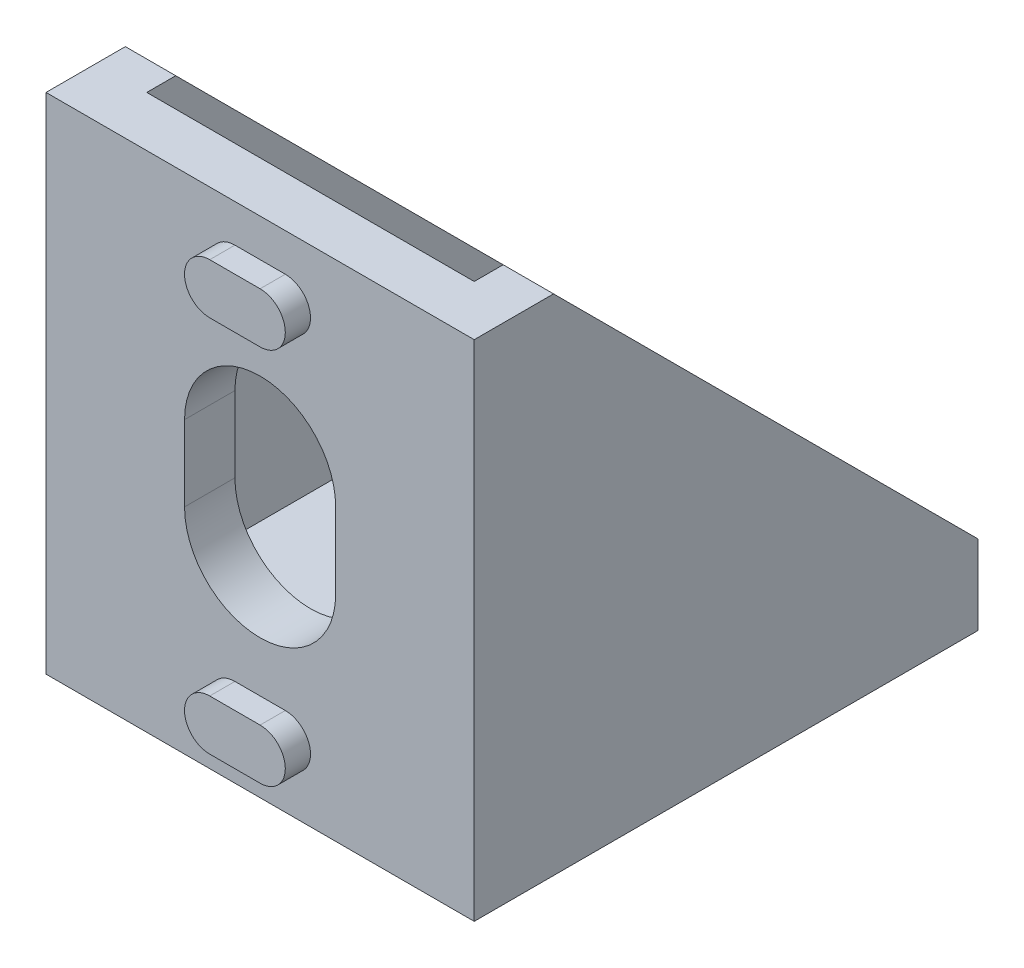
SolidWorks part; units mm, degrees
ref_plane "Front Plane" through (0, 0, 0) normal (0, 0, 1) x (1, 0, 0)
ref_plane "Top Plane" through (0, 0, 0) normal (0, 1, 0) x (1, 0, 0)
ref_plane "Right Plane" through (0, 0, 0) normal (1, 0, 0) x (0, 0, -1)
sketch "Sketch1" plane through (0, 0, 0) normal (1, 0, 0) x (0, 0, -1)
  line L0 (3.15, 20) -> (20, 3.15)
  line L1 (0, 0) -> (20, 0)
  line L2 (0, 0) -> (0, 20)
  line L3 (0, 20) -> (3.15, 20)
  line L4 (20, 0) -> (20, 3.15)
  dimension "D1" = 20
  dimension "D2" = 20
  dimension "D3" = 3.15
  dimension "D4" = 3.15
extrude "Boss-Extrude1" add sketch "Sketch1" along normal blind 2
sketch "Sketch2" plane through (2, 0, 0) normal (1, 0, 0) x (0, 0, -1)
  line L0 (0, 20) -> (0, 0) construction
  line L1 (20, 0) -> (0, 0)
  line L2 (20, 0) -> (20, 3)
  line L3 (20, 3) -> (2, 3)
  line L4 (0, 0) -> (0, 3)
  line L6 (0, 20) -> (2, 20)
  line L7 (0, 20) -> (0, 3)
  line L9 (2, 20) -> (2, 3)
  dimension "D1" = 3
  dimension "D2" = 2
extrude "Boss-Extrude2" add sketch "Sketch2" along normal blind 6.5
sketch "Sketch3" plane through (0, 0, 0) normal (0, 0, 1) x (1, 0, 0)
  line L0 (8.5, 11.5) -> (8.5, 8.5) construction
  line L1 (8.5, 20) -> (8.5, 0) construction
  line L3 (5.5, 11.5) -> (5.5, 8.5)
  line L4 (8.5, 20) -> (0, 20) construction
  line L5 (8.5, 14.5) -> (8.5, 5.5)
  arc A0 (8.5, 14.5) -> (5.5, 11.5) centre (8.5, 11.5) ccw
  arc A1 (5.5, 8.5) -> (8.5, 5.5) centre (8.5, 8.5) ccw
  point P4 (8.5, 10)
  dimension "D2" = 3
  dimension "D1" = 3
  dimension "D3" = 10
extrude "Cut-Extrude1" cut sketch "Sketch3" against normal blind 6.5
sketch "Sketch4" plane through (0, 0, 0) normal (0, -1, 0) x (1, 0, 0)
  line L0 (8.5, -8.5) -> (8.5, -11.5) construction
  line L1 (8.5, 0) -> (8.5, -20) construction
  line L3 (5.5, -8.5) -> (5.5, -11.5)
  line L4 (8.5, 0) -> (0, 0) construction
  line L5 (8.5, -5.5) -> (8.5, -14.5)
  arc A0 (8.5, -5.5) -> (5.5, -8.5) centre (8.5, -8.5) ccw
  arc A1 (5.5, -11.5) -> (8.5, -14.5) centre (8.5, -11.5) ccw
  point P4 (8.5, -10)
  dimension "D1" = 3
  dimension "D2" = 3
  dimension "D3" = 10
extrude "Cut-Extrude2" cut sketch "Sketch4" against normal blind 6.5
sketch "Sketch5" plane through (0, 0, 0) normal (0, -1, 0) x (-1, 0, 0)
  line L0 (-7.5, 2.5) -> (-9.5, 2.5) construction
  line L1 (-7.5, 1.5) -> (-8.5, 1.5)
  line L2 (-7.5, 3.5) -> (-8.5, 3.5)
  line L3 (-8.5, 0) -> (-8.5, 5.5) construction
  line L4 (-8.5, 0) -> (0, 0) construction
  line L5 (0, 10) -> (-12.0266, 10) construction
  line L6 (0, 0) -> (0, 20) construction
  line L7 (-8.5, 1.5) -> (-8.5, 3.5)
  line L8 (-8.5, 18.5) -> (-8.5, 16.5)
  line L9 (-7.5, 16.5) -> (-8.5, 16.5)
  line L10 (-7.5, 18.5) -> (-8.5, 18.5)
  arc A0 (-7.5, 1.5) -> (-7.5, 3.5) centre (-7.5, 2.5) ccw
  arc A1 (-7.5, 18.5) -> (-7.5, 16.5) centre (-7.5, 17.5) cw
  point P2 (-8.5, 2.5)
  dimension "D1" = 1
  dimension "D2" = 2
  dimension "D3" = 0
  dimension "D4" = 2.5
extrude "Boss-Extrude3" add sketch "Sketch5" along normal blind 1
sketch "Sketch6" plane through (0, 0, 0) normal (0, 0, 1) x (1, 0, 0)
  line L0 (7.5, 17.5) -> (9.5, 17.5) construction
  line L1 (7.5, 18.5) -> (8.5, 18.5)
  line L2 (7.5, 16.5) -> (8.5, 16.5)
  line L3 (8.5, 20) -> (8.5, 14.5) construction
  line L4 (8.5, 20) -> (0, 20) construction
  line L5 (8.5, 18.5) -> (8.5, 16.5)
  line L6 (0, 10) -> (5.5, 10) construction
  line L7 (0, 20) -> (0, 0) construction
  line L8 (5.5, 11.5) -> (5.5, 8.5) construction
  line L9 (8.5, 1.5) -> (8.5, 3.5)
  line L10 (7.5, 3.5) -> (8.5, 3.5)
  line L11 (7.5, 1.5) -> (8.5, 1.5)
  arc A0 (7.5, 18.5) -> (7.5, 16.5) centre (7.5, 17.5) ccw
  arc A1 (7.5, 1.5) -> (7.5, 3.5) centre (7.5, 2.5) cw
  point P2 (8.5, 17.5)
  dimension "D2" = 2
  dimension "D3" = 0
  dimension "D4" = 2.5
extrude "Boss-Extrude4" add sketch "Sketch6" along normal blind 1
mirror "Mirror2" about plane through (8.5, 0, 0) normal (1, 0, 0) of bodies 106
